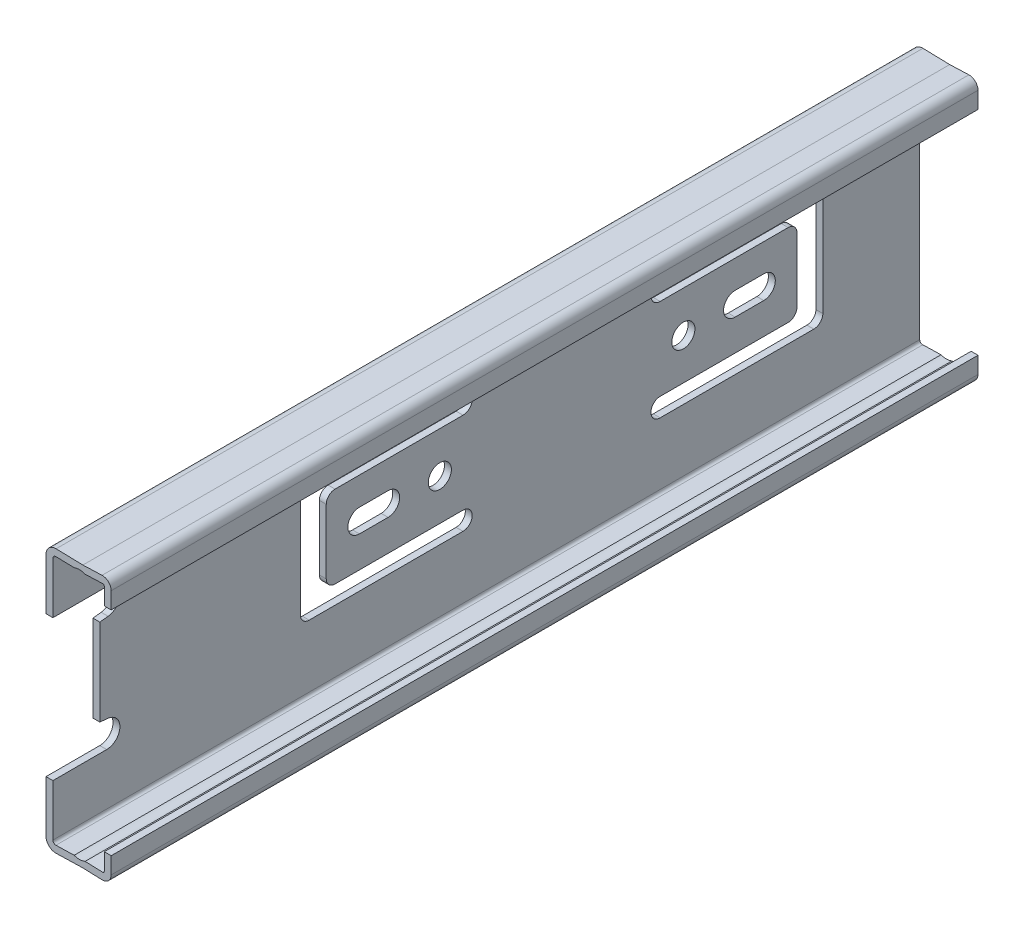
SolidWorks part; units mm, degrees
ref_plane "Front Plane" through (0, 0, 0) normal (0, 0, 1) x (1, 0, 0)
ref_plane "Top Plane" through (0, 0, 0) normal (0, 1, 0) x (1, 0, 0)
ref_plane "Right Plane" through (0, 0, 0) normal (1, 0, 0) x (0, 0, -1)
sketch "Sketch1" plane through (0, 0, 0) normal (0, 0, 1) x (1, 0, 0)
  line L0 (4.445, 18.415) -> (5.6388, 18.415)
  line L1 (5.6388, 18.415) -> (5.6388, 21.2945)
  line L2 (4.0604, 22.8175) -> (0.7433, 22.6989)
  line L3 (0.7433, 22.6989) -> (-3.8925, 22.8203)
  line L4 (-5.6388, 21.1191) -> (-5.6388, -21.1191)
  line L5 (-3.8925, -22.8203) -> (0.7433, -22.6989)
  line L6 (0.7433, -22.6989) -> (4.0604, -22.8175)
  line L7 (4.445, 18.415) -> (4.445, 21.3734)
  line L8 (4.191, 21.6274) -> (1.1312, 21.5182)
  line L9 (-0.7619, 21.5441) -> (-3.9237, 21.6269)
  line L10 (-4.445, 21.1191) -> (-4.445, -21.1191)
  line L11 (-3.9237, -21.6269) -> (-0.7619, -21.5441)
  line L12 (1.1312, -21.5182) -> (4.1819, -21.6273)
  line L13 (4.445, -21.3734) -> (4.445, -18.415)
  line L14 (4.445, -18.415) -> (5.6388, -18.415)
  line L15 (5.6388, -18.415) -> (5.6388, -21.2945)
  arc A0 (5.6388, 21.2945) -> (4.0604, 22.8175) centre (4.1148, 21.2945) ccw
  arc A1 (-3.8925, 22.8203) -> (-5.6388, 21.1191) centre (-3.937, 21.1191) ccw
  arc A2 (-5.6388, -21.1191) -> (-3.8925, -22.8203) centre (-3.937, -21.1191) ccw
  arc A3 (4.445, 21.3734) -> (4.191, 21.6274) centre (4.191, 21.3734) ccw
  arc A5 (1.1312, 21.5182) -> (-0.7619, 21.5441) centre (0.1524, 19.1744) ccw
  arc A6 (-3.9237, 21.6269) -> (-4.445, 21.1191) centre (-3.937, 21.1191) ccw
  arc A8 (-4.445, -21.1191) -> (-3.9237, -21.6269) centre (-3.937, -21.1191) ccw
  arc A9 (-0.7619, -21.5441) -> (1.1312, -21.5182) centre (0.1524, -19.1744) ccw
  arc A10 (4.1819, -21.6273) -> (4.445, -21.3734) centre (4.191, -21.3734) ccw
  arc A33 (4.0604, -22.8175) -> (5.6388, -21.2945) centre (4.1148, -21.2945) ccw
extrude "Boss-Extrude1" add sketch "Sketch1" along normal blind 150
sketch "Sketch2" plane through (-4.445, 0, 0) normal (1, 0, 0) x (0, 0, -1)
  line L0 (-150.087, 12.2088) -> (-150.087, -12.2007)
  line L1 (-150.087, 12.2088) -> (-140.6903, 12.2088)
  line L2 (-140.4485, 7.6496) -> (-141.8828, 7.4971)
  line L3 (-141.8828, 7.4971) -> (-141.8828, -7.4889)
  line L4 (-141.8828, -7.4889) -> (-140.4485, -7.6415)
  line L5 (-140.6903, -12.2007) -> (-150.087, -12.2007)
  arc A0 (-140.6903, 12.2088) -> (-140.4485, 7.6496) centre (-140.6903, 9.9228) cw
  arc A1 (-140.4485, -7.6415) -> (-140.6903, -12.2007) centre (-140.6903, -9.9147) cw
extrude "Cut-Extrude5" cut sketch "Sketch2" against normal through all contours L3 L4 A1 L5 L0 L1 A0 L2
sketch "Sketch3" plane through (-4.445, 0, 0) normal (1, 0, 0) x (0, 0, -1)
  line L0 (-105.6127, 10.2879) -> (-79.0301, 10.2879)
  line L1 (-79.0301, 7.0734) -> (-101.1742, 7.0734)
  line L2 (-141.8828, 0.0041) -> (0, 0) construction
  line L3 (-102.6982, 5.5494) -> (-102.6982, -5.6266)
  line L4 (-101.172, -7.1528) -> (-79.0301, -7.1528)
  line L5 (-79.0301, -10.3256) -> (-105.6523, -10.3256)
  line L6 (-107.1763, -8.8016) -> (-107.1763, 8.7244)
  line L8 (-96.9528, 2.2474) -> (-91.9998, 2.2474)
  line L9 (-91.9998, -1.7526) -> (-96.9528, -1.7526)
  line L10 (-141.8828, 7.4971) -> (-141.8828, -7.4889) construction
  arc A0 (-79.0301, 10.2879) -> (-79.0301, 7.0734) centre (-79.0301, 8.6807) cw
  arc A1 (-101.1742, 7.0734) -> (-102.6982, 5.5494) centre (-101.1742, 5.5494) ccw
  arc A3 (-102.6982, -5.6266) -> (-101.172, -7.1528) centre (-101.172, -5.6266) ccw
  arc A4 (-79.0301, -7.1528) -> (-79.0301, -10.3256) centre (-79.0301, -8.7392) cw
  arc A6 (-105.6523, -10.3256) -> (-107.1763, -8.8016) centre (-105.6523, -8.8016) cw
  arc A8 (-107.1763, 8.7244) -> (-105.6127, 10.2879) centre (-105.6127, 8.7244) cw
  arc A9 (-91.9998, 2.2474) -> (-91.9998, -1.7526) centre (-91.9998, 0.2474) cw
  arc A10 (-96.9528, -1.7526) -> (-96.9528, 2.2474) centre (-96.9528, 0.2474) cw
  circle A11 centre (-83.0463, -0.0386) radius 2
  dimension "D2" = 4
  dimension "D1" = 4.4781
  dimension "D3" = 4
  dimension "D4" = 8.9535
sketch "Sketch6" plane through (-4.445, 0, 0) normal (1, 0, 0) x (0, 0, -1)
  line L0 (-18.3334, -10.3758) -> (-44.916, -10.3758)
  line L1 (-44.916, -7.1613) -> (-22.7719, -7.1613)
  line L2 (17.9367, -0.092) -> (-123.9461, -0.0879) construction
  line L3 (-21.2479, -5.6373) -> (-21.2479, 5.5387)
  line L4 (-22.7741, 7.0649) -> (-44.916, 7.0649)
  line L5 (-44.916, 10.2377) -> (-18.2938, 10.2377)
  line L6 (-16.7698, 8.7137) -> (-16.7698, -8.8123)
  line L8 (-26.9933, -1.7633) -> (-31.9463, -1.7633)
  line L9 (-31.9463, 2.2367) -> (-26.9933, 2.2367)
  arc A0 (-44.916, -10.3758) -> (-44.916, -7.1613) centre (-44.916, -8.7686) cw
  arc A1 (-22.7719, -7.1613) -> (-21.2479, -5.6373) centre (-22.7719, -5.6373) ccw
  arc A3 (-21.2479, 5.5387) -> (-22.7741, 7.0649) centre (-22.7741, 5.5387) ccw
  arc A4 (-44.916, 7.0649) -> (-44.916, 10.2377) centre (-44.916, 8.6513) cw
  arc A6 (-18.2938, 10.2377) -> (-16.7698, 8.7137) centre (-18.2938, 8.7137) cw
  arc A8 (-16.7698, -8.8123) -> (-18.3334, -10.3758) centre (-18.3334, -8.8123) cw
  arc A9 (-31.9463, -1.7633) -> (-31.9463, 2.2367) centre (-31.9463, 0.2367) cw
  arc A10 (-26.9933, 2.2367) -> (-26.9933, -1.7633) centre (-26.9933, 0.2367) cw
  circle A11 centre (-40.8998, -0.0493) radius 2
  dimension "D2" = 4
  dimension "D1" = 4.4781
extrude "Cut-Extrude6" cut sketch "Sketch3" against normal through all both and the other way through all
extrude "Cut-Extrude7" cut sketch "Sketch6" against normal through all both and the other way through all
